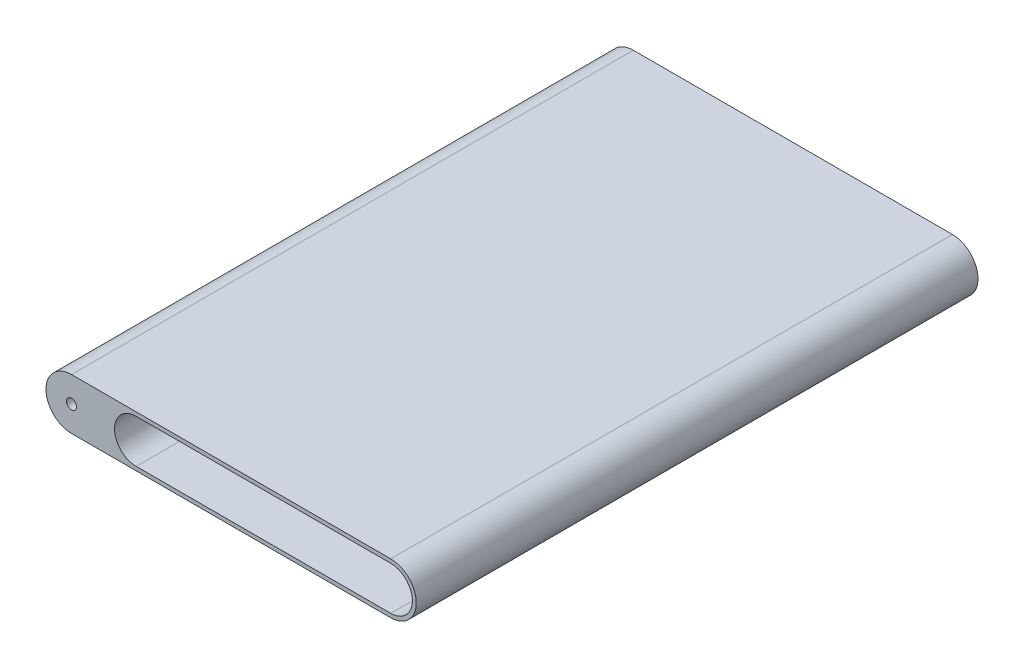
SolidWorks part; units mm, degrees
material "Polyester Resin"
ref_plane "Front Plane" through (0, 0, 0) normal (0, 0, 1) x (1, 0, 0)
ref_plane "Top Plane" through (0, 0, 0) normal (0, 1, 0) x (1, 0, 0)
ref_plane "Right Plane" through (0, 0, 0) normal (1, 0, 0) x (0, 0, -1)
sketch "Sketch2" plane through (0, 0, 0) normal (0, 0, 1) x (1, 0, 0)
  line L0 (0, 0) -> (-635, 0) construction
  line L1 (0, -50.8) -> (-635, -50.8)
  line L2 (0, 50.8) -> (-635, 50.8)
  arc A0 (0, -50.8) -> (0, 50.8) centre (0, 0) ccw
  arc A1 (-635, 50.8) -> (-635, -50.8) centre (-635, 0) ccw
  point P3 (-317.5, 0)
  dimension "D1" = 635
  dimension "D2" = 101.6
extrude "Boss-Extrude2" add sketch "Sketch2" along normal blind 1117.6
sketch "Sketch3" plane through (0, 0, 1117.6) normal (0, 0, 1) x (1, 0, 0)
  line L0 (0, 0) -> (-506.3959, 0) construction
  line L1 (0, -43.1046) -> (-506.3959, -43.1046)
  line L2 (0, 43.1046) -> (-506.3959, 43.1046)
  arc A0 (0, -43.1046) -> (0, 43.1046) centre (0, 0) ccw
  arc A1 (-506.3959, 43.1046) -> (-506.3959, -43.1046) centre (-506.3959, 0) ccw
  circle A2 centre (-635, 0) radius 10
  arc A3 (-635, 50.8) -> (-635, -50.8) centre (-635, 0) ccw construction
  point P3 (-253.1979, 0)
  dimension "D1" = 0
extrude "Cut-Extrude1" cut sketch "Sketch3" against normal blind 1117.6
